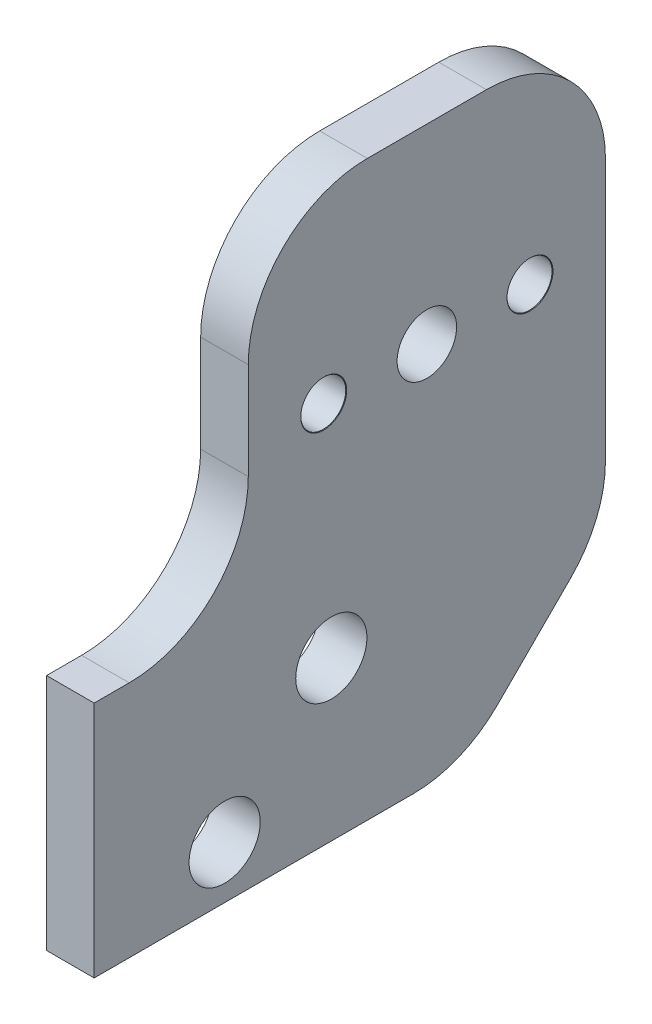
SolidWorks part; units mm, degrees
ref_plane "Front Plane" through (0, 0, 0) normal (0, 0, 1) x (1, 0, 0)
ref_plane "Top Plane" through (0, 0, 0) normal (0, 1, 0) x (1, 0, 0)
ref_plane "Right Plane" through (0, 0, 0) normal (1, 0, 0) x (0, 0, -1)
sketch "Sketch1" plane through (0, 0, 0) normal (1, 0, 0) x (0, 0, -1)
  line L1 (-9.525, 0) -> (9.525, 0)
  line L2 (-9.525, 0) -> (-9.525, 30.5722)
  line L3 (-9.525, 30.5722) -> (9.525, 30.5722)
  line L4 (9.525, 0) -> (9.525, 30.5722)
  point P4 (0, 0)
  dimension "D1" = 19.05
  dimension "D2" = 30.5722
extrude "Boss-Extrude1" add sketch "Sketch1" along normal blind 2.54
sketch "Sketch2" plane through (2.54, 0, 0) normal (1, 0, 0) x (0, 0, -1)
  line L0 (9.525, 30.5722) -> (-9.525, 30.5722) construction
  circle A0 centre (0, 20.4122) radius 1.5875
  dimension "D2" = 3.175
  dimension "D1" = 10.16
extrude "Cut-Extrude1" cut sketch "Sketch2" against normal through all
hole_wizard "M2 Clearance Hole1" positions "Sketch3" profile "Sketch5" hole size "M2" standard "ANSI Metric"
sketch "Sketch3" plane through (2.54, 0, 0) normal (1, 0, 0) x (0, 0, -1)
  line L0 (9.525, 30.5722) -> (-9.525, 30.5722) construction
  point P0 (-5.5, 20.4122)
  point P2 (5.5, 20.4122)
  point P16 (0, 30.5722)
  dimension "D1" = 10.16
  dimension "D2" = 11
  dimension "D3" = 5.5
sketch "Sketch5" plane through (2.54, 20.4122, 5.5) normal (0, 1, 0) x (0, 0, -1)
  line L0 (0, 0) -> (0, 12.721)
  line L1 (0, 12.721) -> (1.2, 12)
  line L2 (1.2, 12) -> (1.2, 0.025)
  line L3 (1.2, 0.025) -> (1.225, 0)
  line L5 (1.225, 0) -> (0, 0)
  line L6 (-1.2, 0.025) -> (-1.225, 0) construction
  line L10 (0, 12.721) -> (-1.2, 12) construction
  line L11 (0, -6.35) -> (0, 107.95) construction
  dimension "Hole Dia." = 2.4
  dimension "Hole Depth" = 12
  dimension "Near C'Sink Dia." = 2.45
  dimension "Near C'Sink Angle" = 90
  dimension "Drill Angle" = 118
sketch "Sketch6" plane through (0, 0, 0) normal (1, 0, 0) x (0, 0, -1)
  line L1 (-9.525, 0) -> (-17.7443, 0)
  line L2 (-9.525, 0) -> (-9.525, 12.7)
  line L3 (-9.525, 12.7) -> (-17.7443, 12.7)
  line L4 (-17.7443, 0) -> (-17.7443, 12.7)
  dimension "D1" = 12.7
  dimension "D2" = 8.2193
extrude "Boss-Extrude2" add sketch "Sketch6" along normal blind 2.54
chamfer "Chamfer1" distance 7.62 angle 45 1 edges at (1.27, 0, -9.525)
fillet "Fillet2" radius 6.35 5 edges at (1.27, 12.7, 9.525) (1.27, 30.5722, 9.525) (1.27, 30.5722, -9.525) (1.27, 7.62, -9.525) (1.27, 0, -1.905)
hole_wizard "#6 Clearance Hole1" positions "Sketch8" profile "Sketch9" hole size "#6" standard "ANSI Inch" end condition through all
sketch "Sketch8" plane through (0, 0, 0) normal (-1, 0, 0) x (0, 0, 1)
  line L0 (17.7443, 0) -> (0.7253, 0) construction
  line L1 (17.7443, 12.7) -> (17.7443, 0) construction
  point P0 (10.7847, 2.794)
  point P2 (5.0951, 8.4582)
  dimension "D1" = 2.794
  dimension "D2" = 5.6642
  dimension "D3" = 6.9596
  dimension "D4" = 5.6896
sketch "Sketch9" plane through (0, 2.794, 10.7847) normal (0, 1, 0) x (0, 0, 1)
  line L0 (0, 0) -> (0, 2.54)
  line L1 (0, 2.54) -> (1.8986, 2.54)
  line L2 (1.8986, 2.54) -> (1.8986, 0)
  line L5 (1.8986, 0) -> (0, 0)
  line L11 (0, -6.35) -> (0, 107.95) construction
  dimension "Thru Hole Dia." = 3.7973
  dimension "Thru Hole Depth" = 2.54
